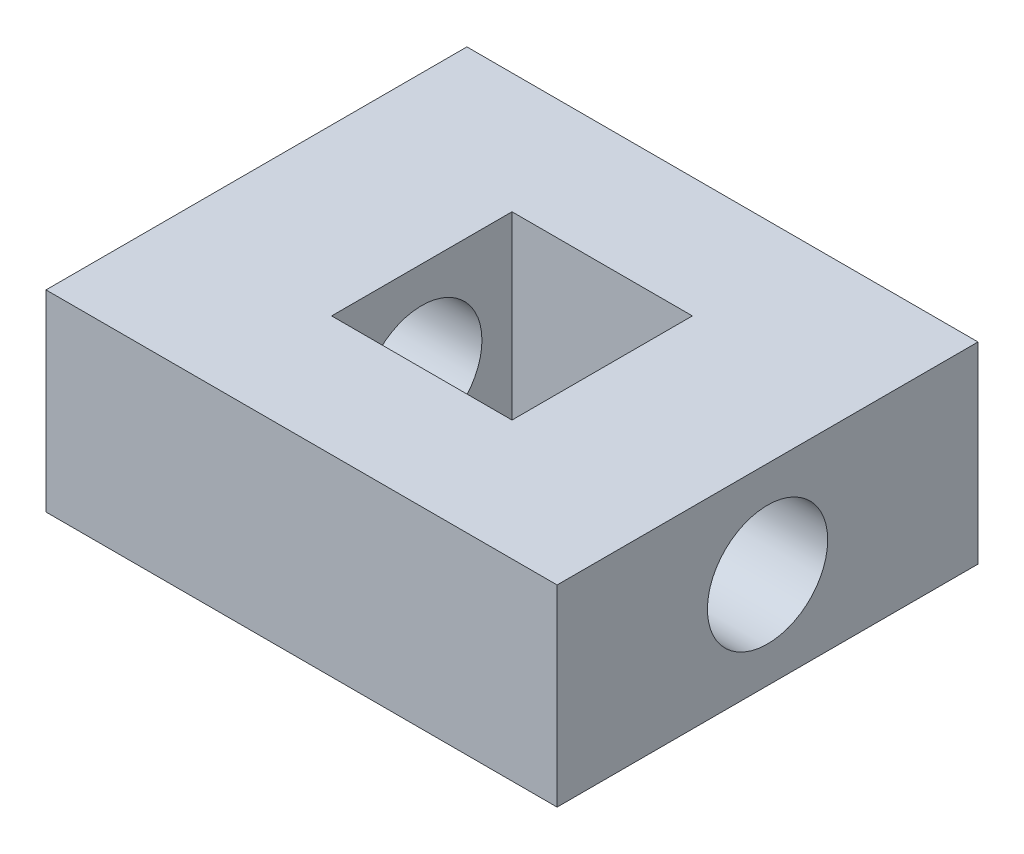
SolidWorks part; units mm, degrees
material "Brass"
ref_plane "Front Plane" through (0, 0, 0) normal (0, 0, 1) x (1, 0, 0)
ref_plane "Top Plane" through (0, 0, 0) normal (0, 1, 0) x (1, 0, 0)
ref_plane "Right Plane" through (0, 0, 0) normal (1, 0, 0) x (0, 0, -1)
sketch "Sketch1" plane through (0, 0, 0) normal (0, 1, 0) x (1, 0, 0)
  line L1 (-8.5, 7) -> (8.5, 7)
  line L2 (-8.5, 7) -> (-8.5, -7)
  line L3 (-8.5, -7) -> (8.5, -7)
  line L4 (8.5, 7) -> (8.5, -7)
  line L5 (-8.5, 7) -> (8.5, -7) construction
  line L6 (-8.5, -7) -> (8.5, 7) construction
  line L7 (-3, 3) -> (3, 3)
  line L8 (-3, 3) -> (-3, -3)
  line L9 (-3, -3) -> (3, -3)
  line L10 (3, 3) -> (3, -3)
  line L11 (-3, 3) -> (3, -3) construction
  line L12 (-3, -3) -> (3, 3) construction
  point P0 (0, 0)
  point P6 (0, 0)
  dimension "D1" = 17
  dimension "D2" = 14
  dimension "D3" = 6
  dimension "6" = 6
extrude "Boss-Extrude1" add sketch "Sketch1" along normal mid plane 6.4 contours L4 L1 L2 L3 L7 L10 L9 L8
sketch "Sketch2" plane through (0, 0, 0) normal (1, 0, 0) x (0, 0, -1)
  circle A0 centre (0, 0) radius 2
  dimension "D1" = 4
extrude "Cut-Extrude1" cut sketch "Sketch2" against normal through all both and the other way through all
cosmetic thread "Cosmetic Thread1" parameters "D2"=5
cosmetic thread "Cosmetic Thread2" parameters "D2"=5
